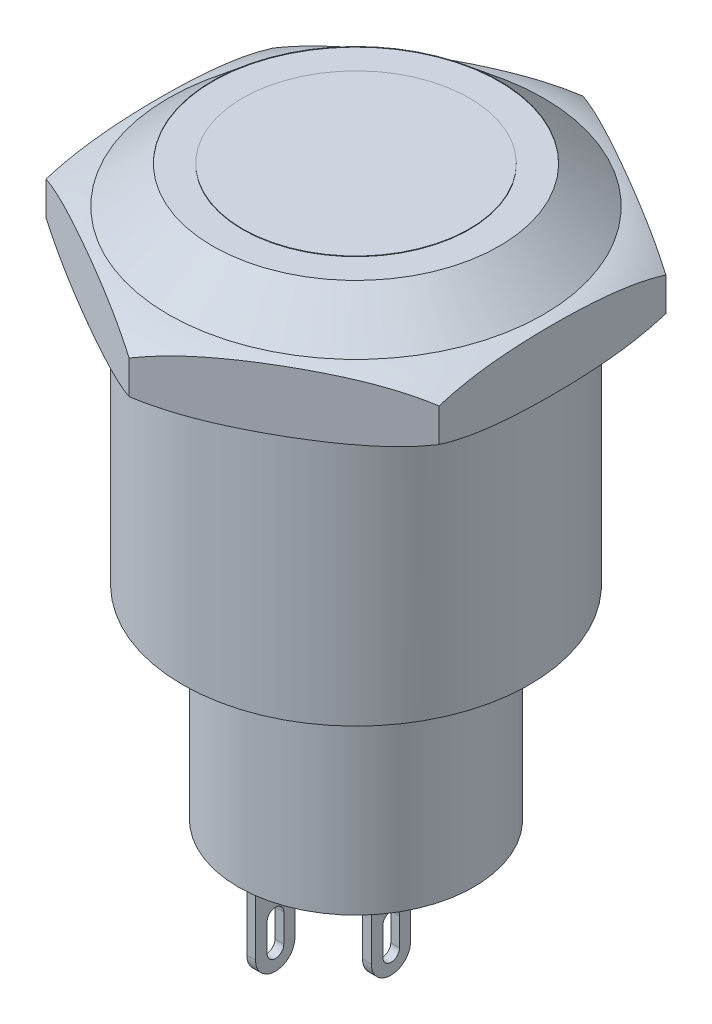
SolidWorks part; units mm, degrees
ref_plane "Front Plane" through (0, 0, 0) normal (0, 0, 1) x (1, 0, 0)
ref_plane "Top Plane" through (0, 0, 0) normal (0, 1, 0) x (1, 0, 0)
ref_plane "Right Plane" through (0, 0, 0) normal (1, 0, 0) x (0, 0, -1)
sketch "Sketch1" plane through (0, 0, 0) normal (0, 1, 0) x (1, 0, 0)
  line L0 (0, 10.3923) -> (0, 0) construction
  line L1 (9, 5.1962) -> (0, 10.3923)
  line L2 (0, 10.3923) -> (-9, 5.1962)
  line L3 (-9, 5.1962) -> (-9, -5.1962)
  line L4 (-9, -5.1962) -> (0, -10.3923)
  line L5 (0, -10.3923) -> (9, -5.1962)
  line L6 (9, -5.1962) -> (9, 5.1962)
  circle A0 centre (0, 0) radius 9 construction
  dimension "D1" = 18
extrude "Boss-Extrude1" add sketch "Sketch1" along normal blind 3.175
sketch "Sketch2" plane through (0, 0, 0) normal (0, -1, 0) x (1, 0, 0)
  circle A0 centre (0, 0) radius 7.95
  dimension "D1" = 15.9
extrude "Boss-Extrude2" add sketch "Sketch2" along normal offset from surface (11.825 mm away) 15 up to face at (0, 3.175, 0)
sketch "Sketch3" plane through (0, -11.825, 0) normal (0, -1, 0) x (1, 0, 0)
  circle A0 centre (0, 0) radius 5.4
  dimension "D1" = 10.8
extrude "Boss-Extrude3" add sketch "Sketch3" along normal offset from surface (9.3 mm away) 24.3 up to face at (0, 3.175, 0)
sketch "Sketch4" plane through (0, -21.125, 0) normal (0, -1, 0) x (1, 0, 0)
  line L0 (-1.4, -2.5) -> (1.4, 0) construction
  line L1 (-1.6, 3.4) -> (-1.2, 3.4)
  line L2 (-1.6, 3.4) -> (-1.6, 1.6)
  line L3 (-1.6, 1.6) -> (-1.2, 1.6)
  line L4 (-1.2, 3.4) -> (-1.2, 1.6)
  line L5 (-1.6, 3.4) -> (-1.2, 1.6) construction
  line L6 (-1.6, 1.6) -> (-1.2, 3.4) construction
  line L7 (-1.6, -1.6) -> (-1.2, -1.6)
  line L8 (-1.6, -1.6) -> (-1.6, -3.4)
  line L9 (-1.6, -3.4) -> (-1.2, -3.4)
  line L10 (-1.2, -1.6) -> (-1.2, -3.4)
  line L11 (-1.6, -1.6) -> (-1.2, -3.4) construction
  line L12 (-1.6, -3.4) -> (-1.2, -1.6) construction
  line L13 (1.2, 0.9) -> (1.6, 0.9)
  line L14 (1.2, 0.9) -> (1.2, -0.9)
  line L15 (1.2, -0.9) -> (1.6, -0.9)
  line L16 (1.6, 0.9) -> (1.6, -0.9)
  line L17 (1.2, 0.9) -> (1.6, -0.9) construction
  line L18 (1.2, -0.9) -> (1.6, 0.9) construction
  line L19 (1.4, 0) -> (-1.4, 2.5) construction
  line L20 (-1.4, 2.5) -> (-1.4, -2.5) construction
  point P0 (-1.4, 2.5)
  point P5 (-1.4, -2.5)
  point P10 (1.4, 0)
  point P17 (-1.4, 0)
  point P19 (0, 1.25)
  dimension "D1" = 1.8
  dimension "D2" = 5
  dimension "D3" = 0.4
  dimension "D4" = 2.8
extrude "Boss-Extrude4" add sketch "Sketch4" along normal offset from surface (5.4 mm away) 29.7 up to face at (0, 3.175, 0)
fillet "Fillet1" radius 0.889 6 edges at (-1.4, -26.525, -3.4) (-1.4, -26.525, -1.6) (1.4, -26.525, 0.9) (1.4, -26.525, -0.9) (-1.4, -26.525, 1.6) (-1.4, -26.525, 3.4)
sketch "Sketch5" plane through (1.6, 0, 0) normal (1, 0, 0) x (0, 0, -1)
  line L0 (0.011, -25.636) -> (0.011, -24.366) construction
  line L1 (-0.37, -25.636) -> (-0.37, -24.366)
  line L2 (0.392, -25.636) -> (0.392, -24.366)
  line L3 (-2.489, -25.636) -> (-2.489, -24.366) construction
  line L4 (-2.87, -25.636) -> (-2.87, -24.366)
  line L5 (-2.108, -25.636) -> (-2.108, -24.366)
  line L6 (2.489, -25.636) -> (2.489, -24.366) construction
  line L7 (2.108, -25.636) -> (2.108, -24.366)
  line L8 (2.87, -25.636) -> (2.87, -24.366)
  arc A0 (-0.37, -25.636) -> (0.392, -25.636) centre (0.011, -25.636) ccw
  arc A1 (0.392, -24.366) -> (-0.37, -24.366) centre (0.011, -24.366) ccw
  arc A2 (-2.87, -25.636) -> (-2.108, -25.636) centre (-2.489, -25.636) ccw
  arc A3 (-2.108, -24.366) -> (-2.87, -24.366) centre (-2.489, -24.366) ccw
  arc A4 (2.108, -25.636) -> (2.87, -25.636) centre (2.489, -25.636) ccw
  arc A5 (2.87, -24.366) -> (2.108, -24.366) centre (2.489, -24.366) ccw
  point P3 (0.011, -25.001)
  point P8 (-2.489, -25.001)
  point P16 (2.489, -25.001)
  dimension "D2" = 0.381
  dimension "D1" = 1.27
extrude "Cut-Extrude1" cut sketch "Sketch5" against normal through all
sketch "Sketch6" plane through (0, 3.175, 0) normal (0, 1, 0) x (1, 0, 0)
  circle A0 centre (0, 0) radius 8.5899
  dimension "D1" = 17.1798
extrude "Boss-Extrude5" add sketch "Sketch6" along normal blind 1.7 draft 50
ref_plane "Plane1" through (0, 1.5875, 0) normal (0, -1, 0) x (1, 0, 0)
sketch "Sketch7" plane through (0, 0, 0) normal (1, 0, 0) x (0, 0, -1)
  line L0 (10.3923, 3.175) -> (10.3923, 0) construction
  line L1 (5.1962, 3.175) -> (10.3923, 3.175) construction
  line L2 (7.8852, 3.175) -> (10.3923, 3.175)
  line L3 (10.3923, 3.175) -> (10.3923, 2.3549)
  line L4 (0, 0) -> (0, 50000) construction
  arc A0 (10.3923, 2.3549) -> (7.8852, 3.175) centre (7.4982, -2.2501) ccw
revolve "Cut-Revolve1" cut sketch "Sketch7" angle 360 about L4
mirror "Mirror1" about plane through (0, 1.5875, 0) normal (0, -1, 0) of "Cut-Revolve1"
sketch "Sketch8" plane through (0, 4.875, 0) normal (0, 1, 0) x (1, 0, 0)
  circle A0 centre (0, 0) radius 6.5639
  circle A1 centre (0, 0) radius 5.1943
  circle A2 centre (0, 0) radius 6.5639 construction
  dimension "D1" = 10.3886
extrude "Cut-Extrude2" cut sketch "Sketch8" against normal blind 0.0254
